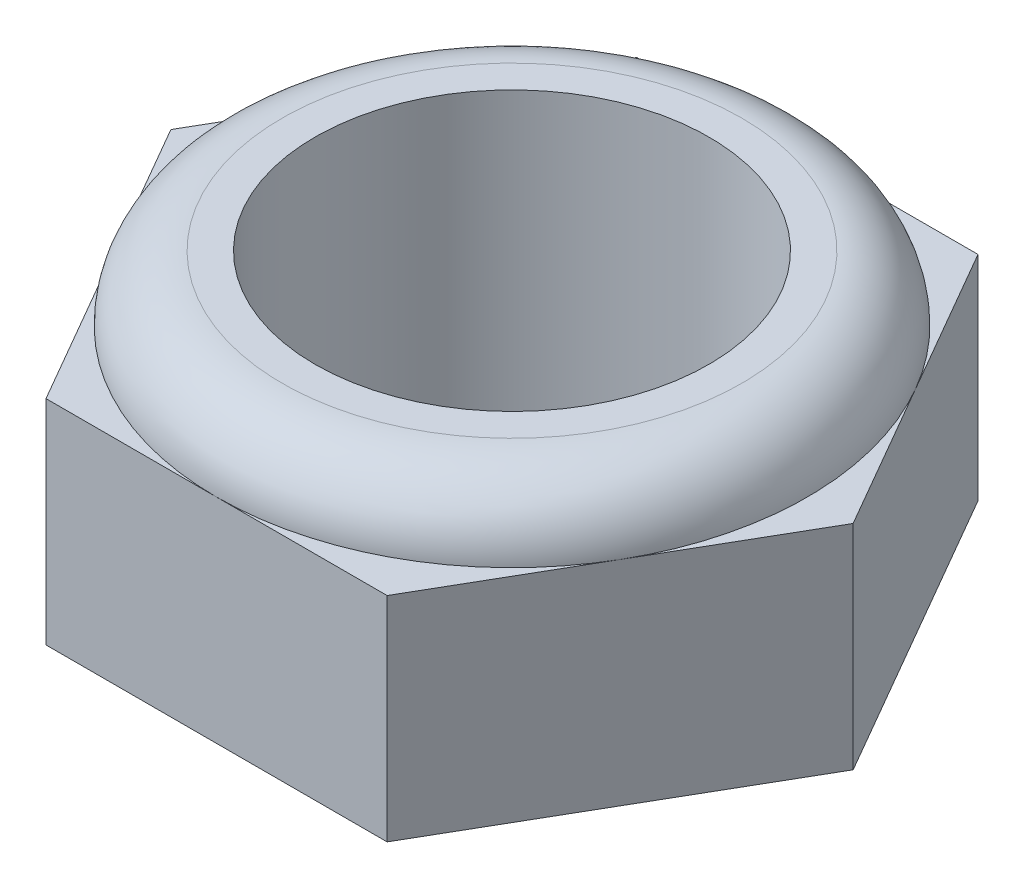
SolidWorks part; units mm, degrees
material "Acier allié"
ref_plane "Face" through (0, 0, 0) normal (0, 0, 1) x (1, 0, 0)
ref_plane "Dessus" through (0, 0, 0) normal (0, 1, 0) x (1, 0, 0)
ref_plane "Droite" through (0, 0, 0) normal (1, 0, 0) x (0, 0, -1)
sketch "Esquisse1" plane through (0, 0, 0) normal (0, 1, 0) x (1, 0, 0)
  line L1 (4.1244, 7.1438) -> (-4.1244, 7.1438)
  line L2 (-4.1244, 7.1438) -> (-8.2489, 0)
  line L3 (-8.2489, 0) -> (-4.1244, -7.1438)
  line L4 (-4.1244, -7.1438) -> (4.1244, -7.1438)
  line L5 (4.1244, -7.1438) -> (8.2489, 0)
  line L6 (8.2489, 0) -> (4.1244, 7.1438)
  circle A0 centre (0, 0) radius 7.1438 construction
  dimension "D1" = 14.2875
extrude "Boss.-Extru.1" add sketch "Esquisse1" along normal blind 6.7469
sketch "Esquisse2" plane through (0, 6.7469, 0) normal (0, 1, 0) x (1, 0, 0)
  circle A0 centre (0, 0) radius 4.7625
  dimension "D1" = 9.525
extrude "Enlèv. mat.-Extru.1" cut sketch "Esquisse2" against normal through all
cosmetic thread "Représentation de filetage1" parameters "D2"=9.5504
sketch "Esquisse3" plane through (0, 0, 0) normal (1, 0, 0) x (0, 0, -1)
  line L0 (-4.7625, 6.7469) -> (-5.5563, 6.7469) construction
  line L1 (-7.1438, 6.7469) -> (0, 6.7469) construction
  line L2 (-7.1438, 6.7469) -> (-7.1438, 0) construction
  line L5 (-7.1438, 6.7469) -> (-6.35, 6.7469)
  line L6 (-6.35, 6.7469) -> (-5.5563, 6.7469)
  line L7 (-7.1438, 5.1594) -> (-8.7313, 5.1594)
  line L8 (-8.7313, 5.1594) -> (-8.7313, 6.7469)
  line L9 (-8.7313, 6.7469) -> (-7.1438, 6.7469)
  line L10 (0, 0) -> (0, 6.7469) construction
  arc A0 (-5.5563, 6.7469) -> (-7.1438, 5.1594) centre (-5.5563, 5.1594) ccw
revolve "Enlèvement de matière-Révolution1" cut sketch "Esquisse3" angle 360 about L10
equation "\"W\"=9/16"
equation "\"D1@Esquisse1\"=\"W\""
equation "\"H\"=17/64"
equation "\"D1@Boss.-Extru.1\"=\"H\""
equation "\"D\"=3/8"
equation "\"D1@Esquisse2\"=\"D\""
equation "\"D2@Représentation de filetage1\"=\"D\"+0.001"
